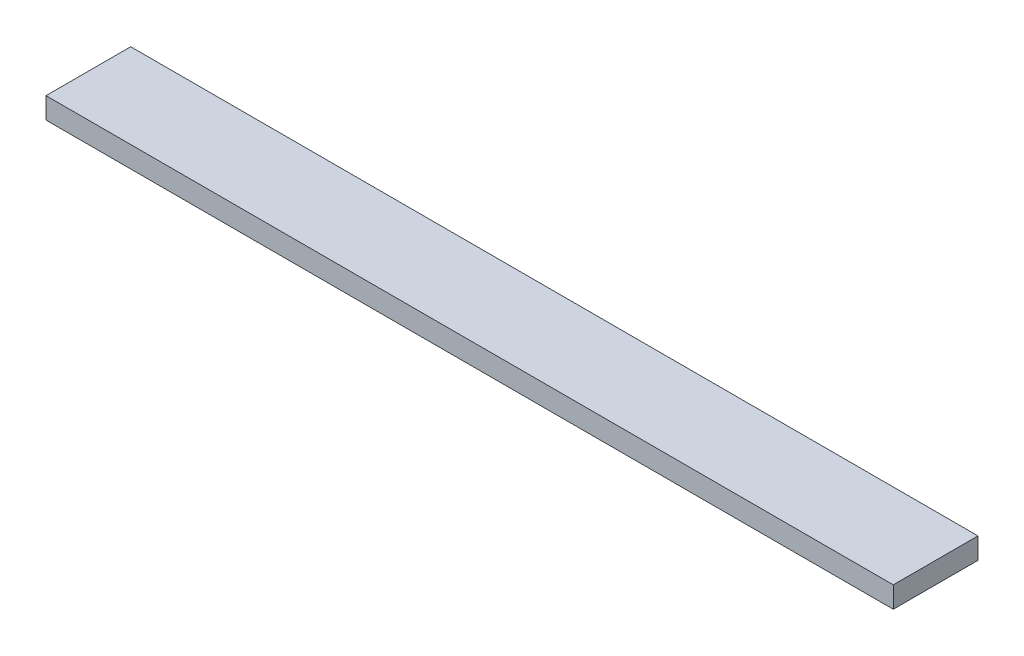
SolidWorks part; units mm, degrees
ref_plane "Front Plane" through (0, 0, 0) normal (0, 0, 1) x (1, 0, 0)
ref_plane "Top Plane" through (0, 0, 0) normal (0, 1, 0) x (1, 0, 0)
ref_plane "Right Plane" through (0, 0, 0) normal (1, 0, 0) x (0, 0, -1)
sketch "Sketch1" plane through (0, 0, 0) normal (0, 0, 1) x (1, 0, 0)
  line L0 (-200, -200) -> (200, -200)
  line L1 (200, -200) -> (200, -190)
  line L2 (200, -200) -> (200, 200) construction
  line L3 (-200, -200) -> (-200, -190)
  line L4 (-200, 200) -> (-200, -200) construction
  line L5 (-200, -190) -> (200, -190)
  dimension "D1" = 10
extrude "Boss-Extrude2" add sketch "Sketch1" along normal blind 40
